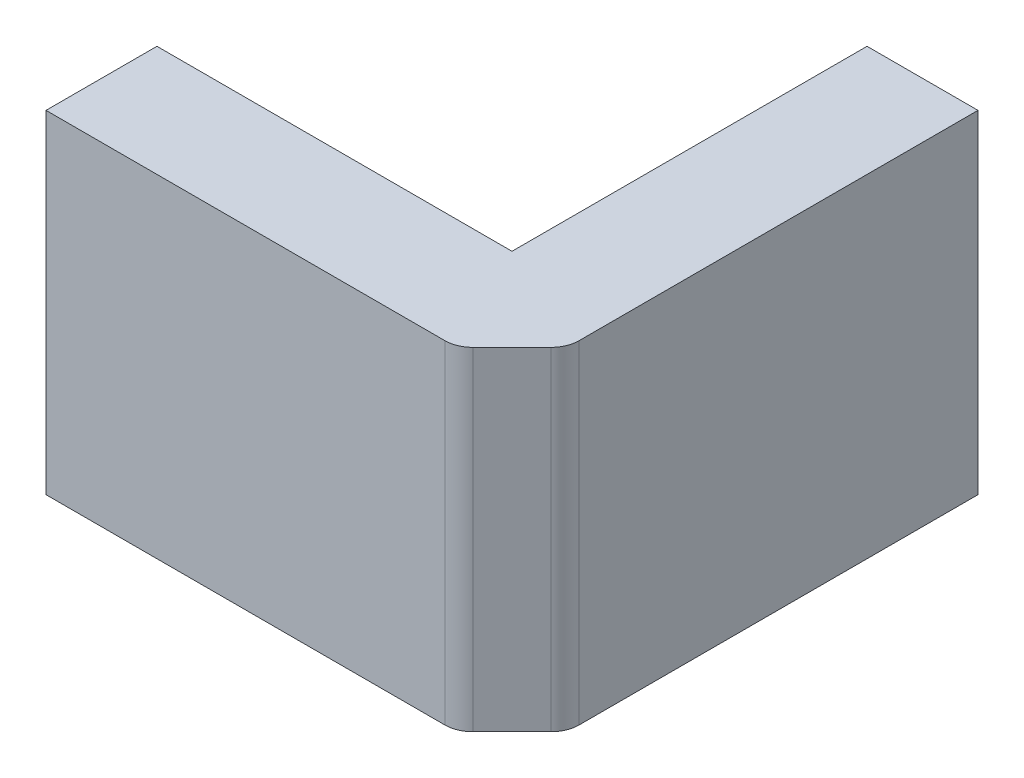
SolidWorks part; units mm, degrees
material "ABS"
ref_plane "Alzado" through (0, 0, 0) normal (0, 0, 1) x (1, 0, 0)
ref_plane "Planta" through (0, 0, 0) normal (0, 1, 0) x (1, 0, 0)
ref_plane "Vista lateral" through (0, 0, 0) normal (1, 0, 0) x (0, 0, -1)
sketch "Sketch1" plane through (0, 0, 0) normal (0, 1, 0) x (1, 0, 0)
  line L0 (22, 42) -> (22, -22)
  line L1 (-42, -42) -> (42, -42)
  line L2 (-42, -42) -> (-42, -22)
  line L3 (22, 42) -> (42, 42)
  line L4 (42, -42) -> (42, 42)
  line L5 (-42, -42) -> (42, 42) construction
  line L6 (-42, 42) -> (42, -42) construction
  line L7 (22, -22) -> (-42, -22)
  point P0 (0, 0)
  dimension "D1" = 64
  dimension "D2" = 64
  dimension "D3" = 20
extrude "Boss-Extrude1" add sketch "Sketch1" along normal blind 60
chamfer "Chamfer1" distance 10 angle 45 1 edges at (42, 30, 42)
fillet "Fillet1" radius 5 2 edges at (42, 30, 32) (32, 30, 42)
